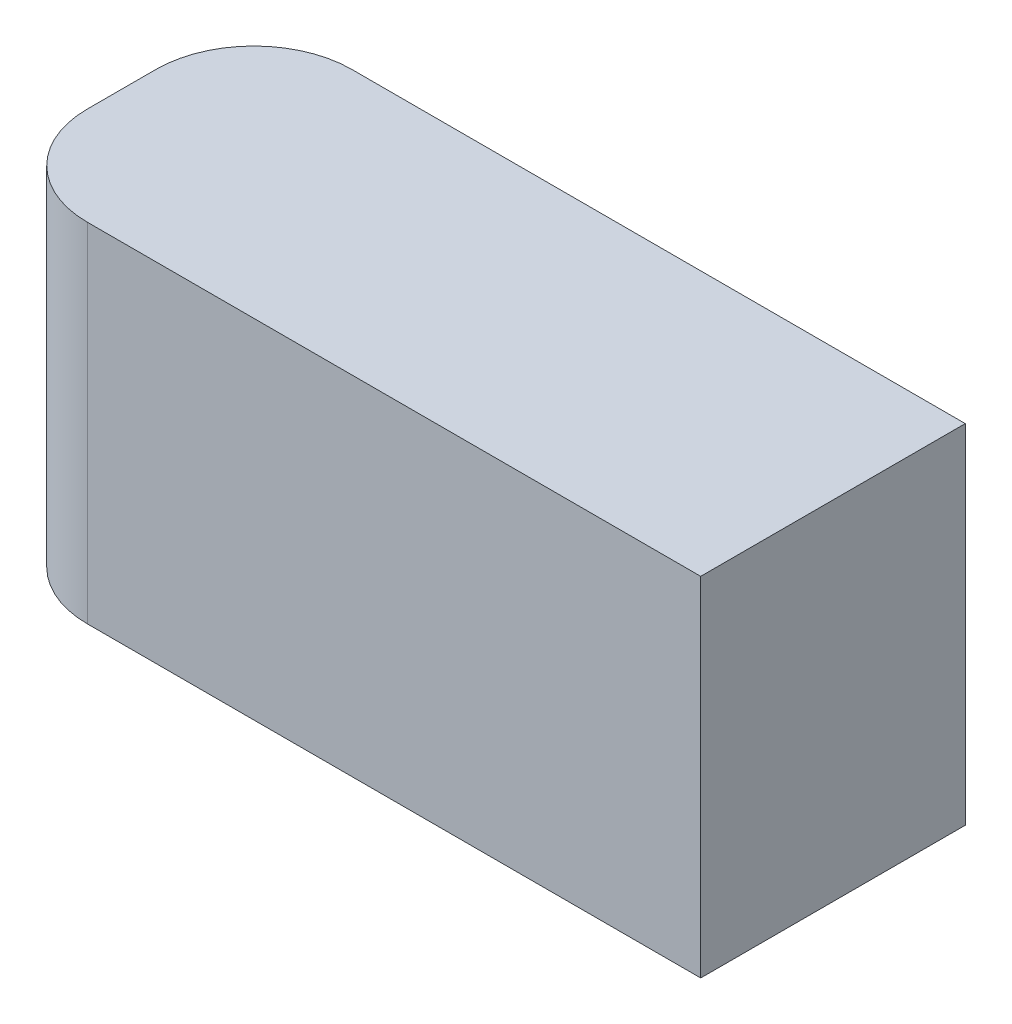
SolidWorks part; units mm, degrees
ref_plane "Front Plane" through (0, 0, 0) normal (0, 0, 1) x (1, 0, 0)
ref_plane "Top Plane" through (0, 0, 0) normal (0, 1, 0) x (1, 0, 0)
ref_plane "Right Plane" through (0, 0, 0) normal (1, 0, 0) x (0, 0, -1)
sketch "Sketch1" plane through (0, 0, 0) normal (0, 0, 1) x (1, 0, 0)
  line L1 (-36.3, -17.75) -> (36.3, -17.75)
  line L2 (-36.3, -17.75) -> (-36.3, 17.75)
  line L3 (-36.3, 17.75) -> (36.3, 17.75)
  line L4 (36.3, -17.75) -> (36.3, 17.75)
  line L5 (-36.3, -17.75) -> (36.3, 17.75) construction
  line L6 (-36.3, 17.75) -> (36.3, -17.75) construction
  point P0 (0, 0)
  dimension "D1" = 72.6
  dimension "D2" = 35.5
extrude "Boss-Extrude1" add sketch "Sketch1" along normal blind 27
fillet "Fillet1" radius 10 2 edges at (-36.3, 0, 0) (-36.3, 0, 27)
